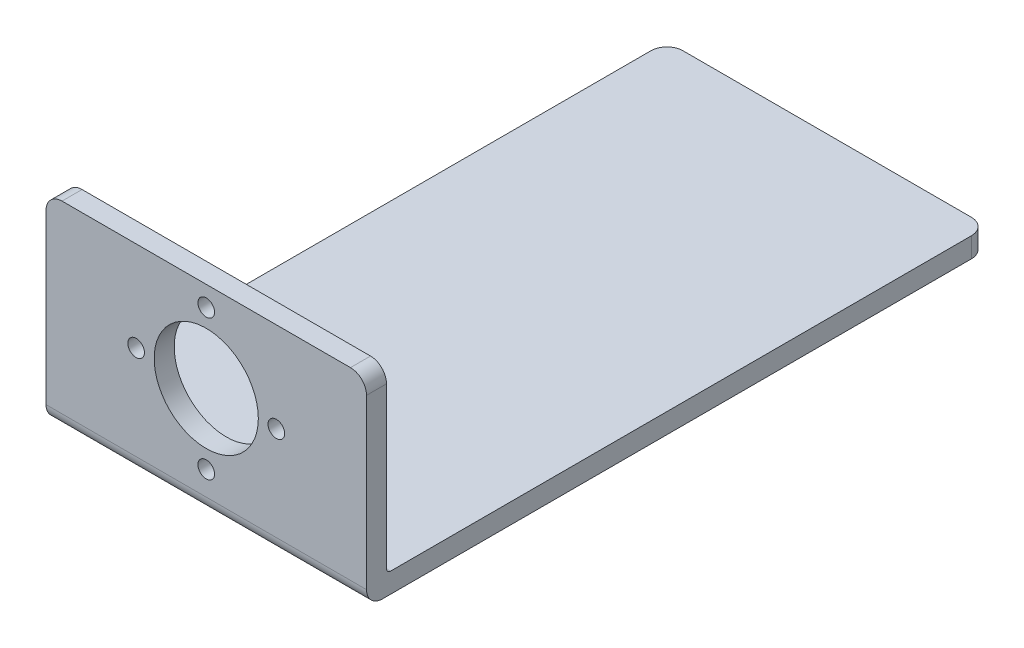
SolidWorks part; units mm, degrees
ref_plane "Front Plane" through (0, 0, 0) normal (0, 0, 1) x (1, 0, 0)
ref_plane "Top Plane" through (0, 0, 0) normal (0, 1, 0) x (1, 0, 0)
ref_plane "Right Plane" through (0, 0, 0) normal (1, 0, 0) x (0, 0, -1)
sketch "Sketch1" plane through (0, 0, 0) normal (0, 0, 1) x (1, 0, 0)
  line L0 (0, 0) -> (0, 17.5) construction
  line L1 (-40, -22.5) -> (40, -22.5)
  line L2 (-40, -22.5) -> (-40, 22.5)
  line L3 (-40, 22.5) -> (40, 22.5)
  line L4 (40, -22.5) -> (40, 22.5)
  line L5 (-40, -22.5) -> (40, 22.5) construction
  line L6 (-40, 22.5) -> (40, -22.5) construction
  circle A0 centre (0, 0) radius 13
  circle A1 centre (0, 17.5) radius 2.075
  circle A2 centre (17.5, 0) radius 2.075
  circle A3 centre (0, -17.5) radius 2.075
  circle A4 centre (-17.5, 0) radius 2.075
  point P0 (0, 0)
  point P6 (0, -22.5)
  point P20 (0, 0)
  dimension "D2" = 26
  dimension "D4" = 4.15
  dimension "D1" = 22.5
  dimension "D3" = 17.5
  dimension "D6" = 80
  dimension "D5" = 4
extrude "Boss-Extrude1" add sketch "Sketch1" along normal blind 5
sketch "Sketch2" plane through (0, 0, 0) normal (0, 0, -1) x (-1, 0, 0)
  line L1 (-40, -22.5) -> (40, -22.5)
  line L2 (-40, -22.5) -> (-40, -27.5)
  line L3 (-40, -27.5) -> (40, -27.5)
  line L4 (40, -22.5) -> (40, -27.5)
  dimension "D1" = 5
  dimension "D2" = 80
extrude "Boss-Extrude2" add sketch "Sketch2" along normal blind 150 and the other way blind 5
fillet "Fillet1" radius 4 5 edges at (0, -27.5, 5) (-40, 22.5, 2.5) (40, 22.5, 2.5) (-40, -25, -150) (40, -25, -150)
fillet "Fillet2" radius 1 1 edges at (0, -22.5, 0)
